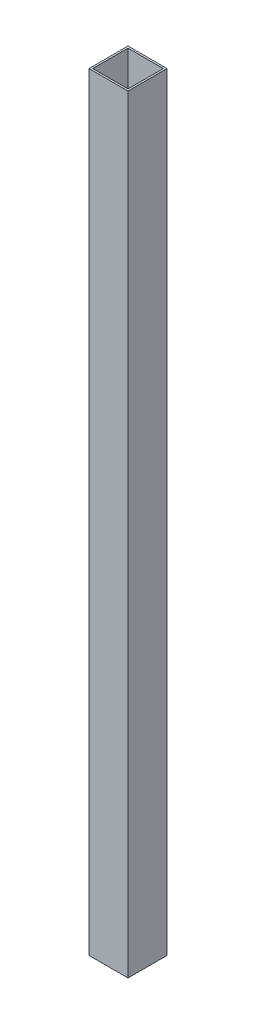
SolidWorks part; units mm, degrees
ref_plane "Front Plane" through (0, 0, 0) normal (0, 0, 1) x (1, 0, 0)
ref_plane "Top Plane" through (0, 0, 0) normal (0, 1, 0) x (1, 0, 0)
ref_plane "Right Plane" through (0, 0, 0) normal (1, 0, 0) x (0, 0, -1)
sketch "Sketch2" plane through (0, 0, 0) normal (0, 1, 0) x (1, 0, 0)
  line L0 (-11.5, 11.5) -> (11.5, 11.5)
  line L1 (-12.7, -12.7) -> (12.7, -12.7)
  line L2 (-12.7, -12.7) -> (-12.7, 12.7)
  line L3 (-12.7, 12.7) -> (12.7, 12.7)
  line L4 (12.7, -12.7) -> (12.7, 12.7)
  line L5 (-12.7, -12.7) -> (12.7, 12.7) construction
  line L6 (-12.7, 12.7) -> (12.7, -12.7) construction
  line L7 (11.5, -11.5) -> (11.5, 11.5)
  line L8 (-11.5, -11.5) -> (11.5, -11.5)
  line L9 (-11.5, -11.5) -> (-11.5, 11.5)
  point P0 (0, 0)
  dimension "D1" = 25.4
  dimension "D3" = 1.2
extrude "Boss-Extrude1" add sketch "Sketch2" along normal mid plane 500
